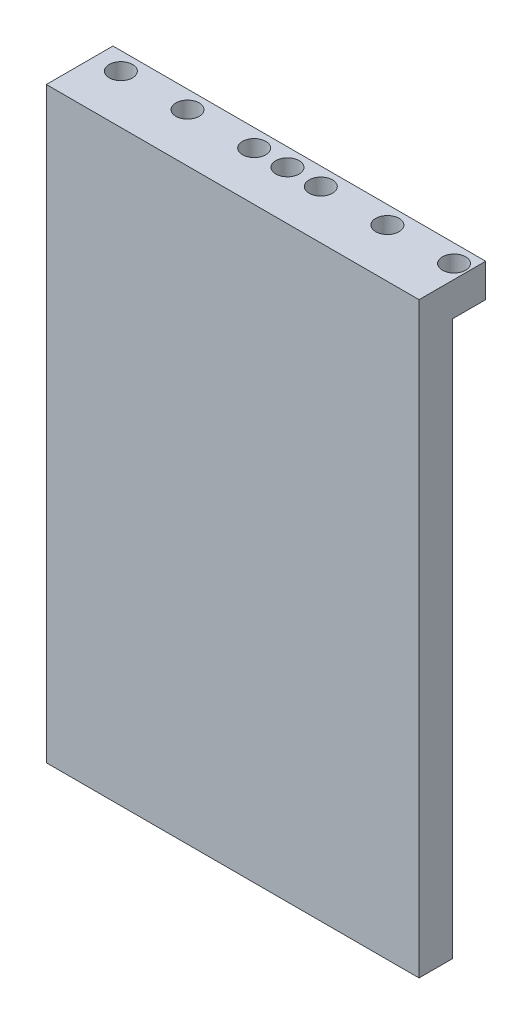
SolidWorks part; units mm, degrees
ref_plane "Plan de face" through (0, 0, 0) normal (1, 0, 0) x (0, 1, 0)
ref_plane "Plan de dessus" through (0, 0, 0) normal (0, 0, 1) x (0, 1, 0)
ref_plane "Plan de droite" through (0, 0, 0) normal (0, 1, 0) x (-1, 0, 0)
sketch "Esquisse1" plane through (0, 0, 0) normal (0, 0, 1) x (0, 1, 0)
  line L1 (-88.1594, -55.9366) -> (88.1594, -55.9366)
  line L2 (-88.1594, -55.9366) -> (-88.1594, 55.9366)
  line L3 (-88.1594, 55.9366) -> (88.1594, 55.9366)
  line L4 (88.1594, -55.9366) -> (88.1594, 55.9366)
  line L5 (-88.1594, -55.9366) -> (88.1594, 55.9366) construction
  line L6 (-88.1594, 55.9366) -> (88.1594, -55.9366) construction
  point P0 (0, 0)
extrude "Boss.-Extru.1" add sketch "Esquisse1" along normal blind 10
sketch "Esquisse2" plane through (0, 88.1594, 0) normal (0, 1, 0) x (-1, 0, 0)
  line L1 (-55.9366, -10) -> (55.9366, -10)
  line L2 (-55.9366, -10) -> (-55.9366, 0)
  line L3 (-55.9366, 0) -> (55.9366, 0)
  line L4 (55.9366, -10) -> (55.9366, 0)
  dimension "10" = 10
extrude "Boss.-Extru.3" add sketch "Esquisse2" against normal blind 10
sketch "Esquisse3" plane through (0, 78.1594, 0) normal (0, -1, 0) x (1, 0, 0)
  circle A0 centre (11.7913, -4.6545) radius 3.5
  circle A1 centre (1.7913, -4.6545) radius 3.5
  circle A2 centre (-8.2087, -4.6545) radius 3.5
  dimension "D1" = 3
extrude "Enlèv. mat.-Extru.1" cut sketch "Esquisse3" against normal blind 10
sketch "Esquisse4" plane through (0, 88.1594, 0) normal (0, 1, 0) x (-1, 0, 0)
  circle A5 centre (-31.7913, -4.6545) radius 3.5
  circle A6 centre (-11.7913, -4.6545) radius 3.5 construction
  circle A7 centre (-1.7913, -4.6545) radius 3.5 construction
  circle A8 centre (8.2087, -4.6545) radius 3.5 construction
  circle A9 centre (28.2087, -4.6545) radius 3.5
  dimension "D1" = 20
  dimension "D2" = 10
  dimension "D3" = 10
  dimension "D4" = 20
extrude "Enlèv. mat.-Extru.2" cut sketch "Esquisse4" against normal blind 10
sketch "Esquisse5" plane through (0, 88.1594, 0) normal (0, 1, 0) x (1, 0, 0)
  circle A0 centre (-48.2087, 4.6545) radius 3.5
  circle A1 centre (-28.2087, 4.6545) radius 3.5 construction
  circle A2 centre (51.7913, 4.6545) radius 3.5
  circle A3 centre (31.7913, 4.6545) radius 3.5 construction
  dimension "D1" = 20
  dimension "D2" = 20
extrude "Enlèv. mat.-Extru.4" cut sketch "Esquisse5" against normal blind 10
